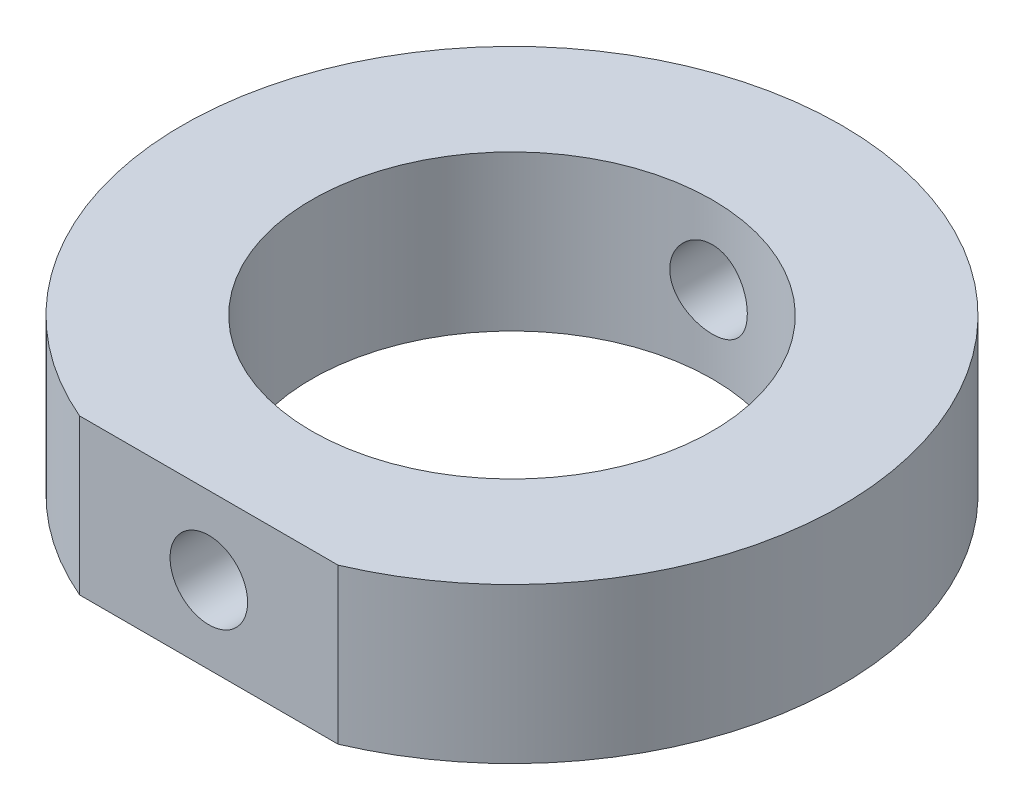
SolidWorks part; units mm, degrees
ref_plane "Front Plane" through (0, 0, 0) normal (0, 0, 1) x (1, 0, 0)
ref_plane "Top Plane" through (0, 0, 0) normal (0, 1, 0) x (1, 0, 0)
ref_plane "Right Plane" through (0, 0, 0) normal (1, 0, 0) x (0, 0, -1)
sketch "Sketch1" plane through (0, 0, 0) normal (0, 1, 0) x (1, 0, 0)
  line L0 (-5, -11.7287) -> (5, -11.7287)
  arc A0 (-5, -11.7287) -> (5, -11.7287) centre (0, 0) cw
  circle A1 centre (0, 0) radius 7.75
  dimension "D1" = 15.5
  dimension "D2" = 5
  dimension "D3" = 10
extrude "Boss-Extrude1" add sketch "Sketch1" along normal blind 6
sketch "Sketch2" plane through (0, 0, 11.7287) normal (0, 0, 1) x (1, 0, 0)
  line L0 (0, 0) -> (0, 6) construction
  line L1 (-5, 6) -> (5, 6) construction
  circle A0 centre (0, 3) radius 1.5
  dimension "D1" = 3
extrude "Cut-Extrude1" cut sketch "Sketch2" against normal through all
